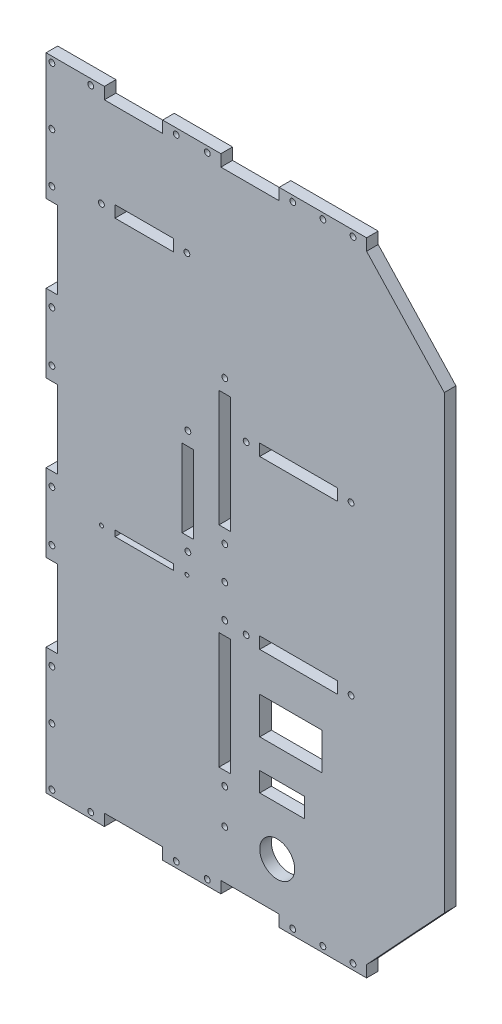
SolidWorks part; units mm, degrees
ref_plane "Plan de face" through (0, 0, 0) normal (0, 0, 1) x (1, 0, 0)
ref_plane "Plan de dessus" through (0, 0, 0) normal (0, 1, 0) x (1, 0, 0)
ref_plane "Plan de droite" through (0, 0, 0) normal (1, 0, 0) x (0, 0, -1)
sketch "Esquisse1" plane through (0, 0, 0) normal (0, 0, 1) x (1, 0, 0)
  line L1 (0, 0) -> (148, 0)
  line L2 (0, 0) -> (0, 330)
  line L3 (0, 330) -> (148, 330)
  line L4 (148, 0) -> (148, 330)
  dimension "D1" = 148
  dimension "D2" = 330
extrude "Boss.-Extru.1" add sketch "Esquisse1" along normal blind 6
sketch "Esquisse2" plane through (0, 0, 6) normal (0, 0, 1) x (1, 0, 0)
  line L1 (0, 0) -> (148, 0) construction
  line L2 (30, 0) -> (60, 0)
  line L3 (30, 0) -> (30, 6)
  line L4 (30, 6) -> (60, 6)
  line L5 (60, 0) -> (60, 6)
  line L6 (0, 330) -> (0, 0) construction
  line L7 (148, 330) -> (0, 330) construction
  line L8 (90, 0) -> (120, 0)
  line L9 (90, 0) -> (90, 6)
  line L10 (90, 6) -> (120, 6)
  line L11 (120, 0) -> (120, 6)
  line L12 (30, 330) -> (60, 330)
  line L13 (30, 330) -> (30, 324)
  line L14 (30, 324) -> (60, 324)
  line L15 (60, 330) -> (60, 324)
  line L17 (90, 330) -> (120, 330)
  line L18 (90, 330) -> (90, 324)
  line L19 (90, 324) -> (120, 324)
  line L20 (120, 330) -> (120, 324)
  line L21 (0, 265) -> (6, 265)
  line L22 (0, 265) -> (0, 225)
  line L23 (0, 225) -> (6, 225)
  line L24 (6, 265) -> (6, 225)
  line L25 (0, 185) -> (6, 185)
  line L26 (0, 185) -> (0, 145)
  line L27 (0, 145) -> (6, 145)
  line L28 (6, 185) -> (6, 145)
  line L29 (0, 105) -> (6, 105)
  line L30 (0, 105) -> (0, 65)
  line L31 (0, 65) -> (6, 65)
  line L32 (6, 105) -> (6, 65)
  dimension "D1" = 6
  dimension "D2" = 30
  dimension "D3" = 30
  dimension "D4" = 30
  dimension "D5" = 30
  dimension "D6" = 6
  dimension "D7" = 6
  dimension "D8" = 65
  dimension "D9" = 40
  dimension "D10" = 40
  dimension "D11" = 40
  dimension "D12" = 40
  dimension "D13" = 40
extrude "Enlèv. mat.-Extru.1" cut sketch "Esquisse2" against normal blind 6
sketch "Esquisse5" plane through (0, 0, 6) normal (0, 0, 1) x (1, 0, 0)
  line L0 (0, 65) -> (0, 0) construction
  line L1 (35.5, 280) -> (65.5, 280)
  line L2 (35.5, 280) -> (35.5, 274)
  line L3 (142, 99) -> (110, 99)
  line L4 (142, 99) -> (142, 80)
  line L5 (142, 80) -> (110, 80)
  line L6 (110, 99) -> (110, 80)
  line L7 (133, 65) -> (110, 65)
  line L8 (133, 65) -> (133, 55)
  line L9 (133, 55) -> (110, 55)
  line L10 (110, 65) -> (110, 55)
  line L11 (35.5, 274) -> (65.5, 274)
  line L12 (65.5, 280) -> (65.5, 274)
  line L13 (0, 145) -> (0, 105) construction
  line L14 (120, 0) -> (148, 0) construction
  line L15 (0, 330) -> (0, 265) construction
  line L16 (30, 330) -> (0, 330) construction
  line L17 (0, 225) -> (0, 185) construction
  line L18 (120, 0) -> (148, 0) construction
  line L19 (35.5, 135) -> (65.5, 135)
  line L20 (35.5, 135) -> (35.5, 132)
  line L21 (35.5, 132) -> (65.5, 132)
  line L22 (65.5, 135) -> (65.5, 132)
  circle A0 centre (119, 30) radius 9
  dimension "D2" = 18
  dimension "D5" = 55
  dimension "D11" = 30
  dimension "D3" = 32
  dimension "D4" = 19
  dimension "D6" = 119
  dimension "D7" = 10
  dimension "D8" = 23
  dimension "D9" = 15
  dimension "D10" = 110
  dimension "D12" = 110
  dimension "D13" = 30
  dimension "D14" = 35.5
  dimension "D15" = 50
  dimension "D16" = 6
  dimension "D17" = 3
  dimension "D18" = 30
  dimension "D19" = 35.5
  dimension "D20" = 139
extrude "Enlèv. mat.-Extru.3" cut sketch "Esquisse5" against normal blind 6
sketch "Esquisse6" plane through (0, 0, 6) normal (0, 0, 1) x (1, 0, 0)
  line L1 (0, 145) -> (0, 105) construction
  line L2 (95, 116) -> (89, 116)
  line L3 (95, 116) -> (95, 56)
  line L4 (95, 56) -> (89, 56)
  line L13 (89, 116) -> (89, 56)
  line L14 (60, 0) -> (90, 0) construction
  line L15 (95, 224) -> (89, 224)
  line L16 (95, 224) -> (95, 164)
  line L17 (95, 164) -> (89, 164)
  line L18 (89, 224) -> (89, 164)
  dimension "D2" = 6
  dimension "D5" = 6
  dimension "D12" = 56
  dimension "D13" = 48
  dimension "D14" = 60
  dimension "D15" = 60
  dimension "D16" = 89
  dimension "D17" = 89
extrude "Enlèv. mat.-Extru.4" cut sketch "Esquisse6" against normal blind 10
sketch "Esquisse8" plane through (148, 0, 0) normal (1, 0, 0) x (0, 0, -1)
  line L1 (-6, 330) -> (0, 330)
  line L2 (-6, 330) -> (-6, 0)
  line L3 (-6, 0) -> (0, 0)
  line L4 (0, 330) -> (0, 0)
extrude "Boss.-Extru.2" add sketch "Esquisse8" along normal blind 57
sketch "Esquisse9" plane through (0, 0, 6) normal (0, 0, 1) x (1, 0, 0)
  line L0 (165, 0) -> (205, 0)
  line L1 (120, 0) -> (205, 0) construction
  line L2 (205, 0) -> (205, 49)
  line L3 (205, 330) -> (205, 0) construction
  line L4 (165, 0) -> (165, 6)
  line L5 (165, 330) -> (205, 330)
  line L6 (205, 330) -> (120, 330) construction
  line L7 (205, 330) -> (205, 281)
  line L8 (165, 330) -> (165, 324)
  line L9 (165, 6) -> (205, 49)
  line L10 (165, 324) -> (205, 281)
  dimension "D1" = 40
  dimension "D2" = 49
  dimension "D3" = 40
  dimension "D4" = 49
  dimension "D5" = 6
  dimension "D6" = 6
extrude "Enlèv. mat.-Extru.5" cut sketch "Esquisse9" against normal through all
sketch "Esquisse10" plane through (0, 0, 6) normal (0, 0, 1) x (1, 0, 0)
  line L0 (90, 330) -> (60, 330) construction
  line L1 (76, 191) -> (70, 191)
  line L2 (76, 191) -> (76, 151)
  line L3 (76, 151) -> (70, 151)
  line L4 (70, 191) -> (70, 151)
  line L9 (205, 49) -> (205, 281) construction
  line L10 (110, 211) -> (150, 211)
  line L11 (0, 225) -> (0, 185) construction
  line L13 (110, 211) -> (110, 205)
  line L14 (110, 205) -> (150, 205)
  line L15 (150, 211) -> (150, 205)
  line L16 (165, 330) -> (120, 330) construction
  line L18 (110, 125) -> (150, 125)
  line L19 (110, 125) -> (110, 119)
  line L20 (110, 119) -> (150, 119)
  line L21 (150, 125) -> (150, 119)
  dimension "D1" = 40
  dimension "D4" = 139
  dimension "D5" = 70
  dimension "D8" = 6
  dimension "D9" = 40
  dimension "D10" = 55
  dimension "D11" = 6
  dimension "D12" = 119
  dimension "D13" = 6
  dimension "D14" = 40
  dimension "D15" = 55
  dimension "D16" = 80
extrude "Enlèv. mat.-Extru.6" cut sketch "Esquisse10" against normal through all
sketch "Esquisse11" plane through (0, 0, 6) normal (0, 0, 1) x (1, 0, 0)
  line L0 (165, 330) -> (120, 330) construction
  line L1 (165, 330) -> (165, 324) construction
  line L2 (120, 324) -> (120, 330) construction
  line L3 (90, 330) -> (90, 324) construction
  line L4 (90, 330) -> (60, 330) construction
  line L5 (60, 324) -> (60, 330) construction
  line L6 (30, 330) -> (30, 324) construction
  line L7 (30, 330) -> (0, 330) construction
  line L8 (0, 330) -> (0, 265) construction
  line L9 (6, 265) -> (0, 265) construction
  line L10 (35.5, 280) -> (35.5, 274) construction
  line L11 (65.5, 280) -> (35.5, 280) construction
  line L12 (65.5, 274) -> (65.5, 280) construction
  line L13 (0, 225) -> (6, 225) construction
  line L14 (0, 225) -> (0, 185) construction
  line L15 (6, 185) -> (0, 185) construction
  line L18 (76, 151) -> (76, 191) construction
  line L19 (70, 151) -> (76, 151) construction
  line L20 (95, 224) -> (89, 224) construction
  line L21 (89, 224) -> (89, 164) construction
  line L22 (89, 164) -> (95, 164) construction
  line L23 (110, 205) -> (150, 205) construction
  line L24 (89, 116) -> (89, 56) construction
  line L25 (95, 116) -> (89, 116) construction
  line L26 (95, 164) -> (95, 224) construction
  line L27 (89, 56) -> (95, 56) construction
  line L28 (95, 56) -> (95, 116) construction
  line L29 (35.5, 135) -> (35.5, 132) construction
  line L30 (0, 145) -> (6, 145) construction
  line L31 (0, 145) -> (0, 105) construction
  line L32 (6, 105) -> (0, 105) construction
  line L33 (35.5, 132) -> (65.5, 132) construction
  line L34 (0, 65) -> (6, 65) construction
  line L35 (0, 65) -> (0, 0) construction
  line L36 (0, 0) -> (30, 0) construction
  line L37 (30, 6) -> (30, 0) construction
  line L38 (60, 0) -> (60, 6) construction
  line L39 (60, 0) -> (90, 0) construction
  line L40 (90, 6) -> (90, 0) construction
  line L41 (120, 0) -> (165, 0) construction
  line L42 (120, 0) -> (120, 6) construction
  line L43 (165, 6) -> (165, 0) construction
  line L44 (110, 211) -> (110, 205) construction
  line L45 (150, 205) -> (150, 211) construction
  line L46 (110, 119) -> (150, 119) construction
  line L47 (150, 119) -> (150, 125) construction
  line L48 (150, 125) -> (110, 125) construction
  line L49 (110, 125) -> (110, 119) construction
  line L50 (65.5, 135) -> (35.5, 135) construction
  line L51 (65.5, 132) -> (65.5, 135) construction
  line L52 (76, 151) -> (76, 191) construction
  line L53 (76, 191) -> (70, 191) construction
  circle A0 centre (158, 327) radius 1.5
  circle A1 centre (142.5, 327) radius 1.5
  circle A2 centre (127, 327) radius 1.5
  circle A3 centre (67, 327) radius 1.5
  circle A4 centre (83, 327) radius 1.5
  circle A5 centre (3, 327) radius 1.5
  circle A6 centre (23, 327) radius 1.5
  circle A7 centre (3, 297.5) radius 1.5
  circle A8 centre (3, 272) radius 1.5
  circle A9 centre (3, 218) radius 1.5
  circle A10 centre (3, 192) radius 1.5
  circle A11 centre (3, 138) radius 1.5
  circle A12 centre (3, 112) radius 1.5
  circle A13 centre (3, 58) radius 1.5
  circle A14 centre (3, 3) radius 1.5
  circle A15 centre (3, 32.5) radius 1.5
  circle A16 centre (23, 3) radius 1.5
  circle A17 centre (67, 3) radius 1.5
  circle A18 centre (83, 3) radius 1.5
  circle A19 centre (127, 3) radius 1.5
  circle A20 centre (158, 3) radius 1.5
  circle A21 centre (142.5, 3) radius 1.5
  circle A22 centre (92, 231) radius 1.5
  circle A23 centre (92, 157) radius 1.5
  circle A24 centre (92, 123) radius 1.5
  circle A25 centre (92, 49) radius 1.5
  circle A26 centre (92, 140) radius 1.5
  circle A27 centre (73, 144) radius 1.5
  circle A28 centre (73, 198) radius 1.5
  circle A29 centre (28.5, 133.5) radius 1.005
  circle A30 centre (72.5, 133.5) radius 1.005
  circle A31 centre (72.5, 277) radius 1.5
  circle A32 centre (28.5, 277) radius 1.5
  circle A33 centre (92, 31) radius 1.5
  circle A34 centre (103, 208) radius 1.5
  circle A35 centre (157, 208) radius 1.5
  circle A36 centre (157, 122) radius 1.5
  circle A37 centre (103, 122) radius 1.5
  point P74 (90, 327)
  point P89 (35.5, 277)
  point P96 (3, 225)
  point P130 (3, 145)
  point P139 (3, 65)
  point P144 (3, 65)
  point P147 (30, 3)
  point P161 (120, 3)
  point P162 (165, 3)
  dimension "D1" = 3
  dimension "D2" = 3
  dimension "D3" = 7
  dimension "D4" = 3
  dimension "D5" = 3
  dimension "D6" = 3
  dimension "D7" = 7
  dimension "D8" = 3
  dimension "D10" = 3
  dimension "D11" = 7
  dimension "D12" = 3
  dimension "D13" = 3
  dimension "D14" = 3
  dimension "D15" = 7
  dimension "D16" = 3
  dimension "D17" = 7
  dimension "D18" = 3
  dimension "D19" = 3
  dimension "D20" = 3
  dimension "D21" = 3
  dimension "D22" = 3
  dimension "D23" = 3
  dimension "D26" = 7
  dimension "D27" = 3
  dimension "D28" = 3
  dimension "D29" = 7
  dimension "D30" = 3
  dimension "D31" = 3
  dimension "D32" = 3
  dimension "D33" = 7
  dimension "D34" = 3
  dimension "D35" = 7
  dimension "D36" = 3
  dimension "D37" = 3
  dimension "D38" = 3
  dimension "D39" = 7
  dimension "D40" = 3
  dimension "D41" = 3
  dimension "D42" = 7
  dimension "D43" = 3
  dimension "D44" = 3
  dimension "D45" = 7
  dimension "D46" = 3
  dimension "D47" = 7
  dimension "D48" = 3
  dimension "D49" = 3
  dimension "D50" = 3
  dimension "D51" = 7
  dimension "D52" = 3
  dimension "D53" = 3
  dimension "D54" = 7
  dimension "D55" = 3
  dimension "D56" = 24
  dimension "D57" = 3
  dimension "D58" = 3
  dimension "D59" = 7
  dimension "D60" = 3
  dimension "D61" = 3
  dimension "D62" = 25
  dimension "D63" = 3
  dimension "D64" = 2.01
  dimension "D65" = 2.01
  dimension "D66" = 7
  dimension "D67" = 3
  dimension "D68" = 7
  dimension "D69" = 3
  dimension "D70" = 3
  dimension "D71" = 7
  dimension "D72" = 3
  dimension "D73" = 1.5
  dimension "D74" = 1.5
  dimension "D75" = 7
  dimension "D76" = 3
  dimension "D77" = 7
  dimension "D78" = 3
  dimension "D79" = 3
  dimension "D80" = 3
  dimension "D81" = 32.5
  dimension "D82" = 3
  dimension "D83" = 3
  dimension "D84" = 3
  dimension "D85" = 3
  dimension "D86" = 3
  dimension "D87" = 7
  dimension "D88" = 3
  dimension "D89" = 3
  dimension "D90" = 7
  dimension "D91" = 3
  dimension "D92" = 3
  dimension "D93" = 7
  dimension "D95" = 22.5
  dimension "D96" = 3
  dimension "D97" = 3
  dimension "D98" = 3
  dimension "D99" = 7
  dimension "D100" = 3
  dimension "D101" = 3
  dimension "D102" = 7
  dimension "D103" = 3
  dimension "D104" = 3
  dimension "D105" = 7
  dimension "D106" = 3
  dimension "D107" = 7
  dimension "D108" = 3
  dimension "D109" = 3
  dimension "D110" = 3
  dimension "D111" = 7
  dimension "D112" = 3
  dimension "D113" = 3
  dimension "D114" = 7
  dimension "D9" = 22.5
  dimension "D24" = 3
  dimension "D25" = 32.5
  dimension "D94" = 3
extrude "Enlèv. mat.-Extru.7" cut sketch "Esquisse11" against normal through all
sketch "Esquisse12" plane through (0, 0, 0) normal (0, 0, -1) x (-1, 0, 0)
  circle A0 centre (-158, 327) radius 2.995
  circle A1 centre (-142.5, 327) radius 2.995
  circle A2 centre (-127, 327) radius 2.995
  circle A3 centre (-83, 327) radius 2.995
  circle A4 centre (-67, 327) radius 2.995
  circle A5 centre (-23, 327) radius 2.995
  circle A6 centre (-3, 327) radius 2.995
  circle A7 centre (-3, 297.5) radius 2.995
  circle A8 centre (-3, 272) radius 2.995
  circle A9 centre (-28.5, 277) radius 3
  circle A10 centre (-72.5, 277) radius 3
  circle A11 centre (-92, 231) radius 3
  circle A12 centre (-103, 208) radius 3
  circle A13 centre (-73, 144) radius 3
  circle A14 centre (-3, 218) radius 2.995
  circle A15 centre (-3, 192) radius 2.995
  circle A16 centre (-73, 198) radius 3
  circle A17 centre (-92, 157) radius 3
  circle A18 centre (-92, 140) radius 3
  circle A19 centre (-92, 123) radius 3
  circle A20 centre (-72.5, 133.5) radius 2
  circle A21 centre (-28.5, 133.5) radius 2
  circle A22 centre (-3, 112) radius 2.995
  circle A23 centre (-3, 138) radius 2.995
  circle A24 centre (-3, 58) radius 2.995
  circle A25 centre (-3, 32.5) radius 2.995
  circle A26 centre (-3, 3) radius 2.995
  circle A27 centre (-23, 3) radius 2.995
  circle A28 centre (-67, 3) radius 2.995
  circle A29 centre (-83, 3) radius 2.995
  circle A30 centre (-92, 31) radius 3
  circle A31 centre (-92, 49) radius 3
  circle A32 centre (-127, 3) radius 2.995
  circle A33 centre (-142.5, 3) radius 2.995
  circle A34 centre (-157, 208) radius 3
  circle A35 centre (-158, 3) radius 2.995
  circle A36 centre (-157, 122) radius 3
  circle A37 centre (-103, 122) radius 3
  dimension "D1" = 5.99
  dimension "D2" = 5.99
  dimension "D3" = 5.99
  dimension "D4" = 5.99
  dimension "D5" = 5.99
  dimension "D6" = 6
  dimension "D7" = 6
  dimension "D8" = 5.99
  dimension "D9" = 5.99
  dimension "D10" = 5.99
  dimension "D11" = 5.99
  dimension "D12" = 6
  dimension "D13" = 5.99
  dimension "D14" = 6
  dimension "D15" = 6
  dimension "D16" = 5.99
  dimension "D17" = 5.99
  dimension "D18" = 5.99
  dimension "D19" = 4
  dimension "D20" = 4
  dimension "D21" = 6
  dimension "D22" = 6
  dimension "D23" = 6
  dimension "D24" = 6
  dimension "D25" = 6
  dimension "D26" = 5.99
  dimension "D27" = 5.99
  dimension "D28" = 5.99
  dimension "D29" = 5.99
  dimension "D30" = 5.99
  dimension "D31" = 5.99
  dimension "D32" = 5.99
  dimension "D33" = 5.99
  dimension "D34" = 5.99
  dimension "D35" = 6
  dimension "D36" = 6
  dimension "D37" = 6
  dimension "D38" = 6
extrude "Enlèv. mat.-Extru.8" cut sketch "Esquisse12" against normal blind 3
